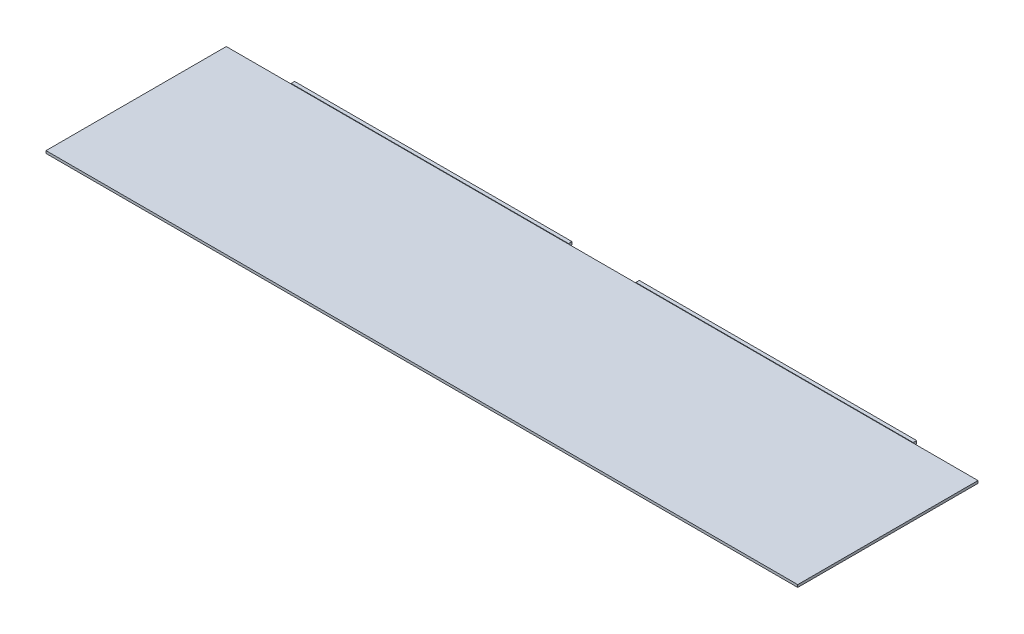
SolidWorks part; units mm, degrees
material "6061-T6 (SS)"
ref_plane "X-Y Datum" through (0, 0, 0) normal (0, 0, 1) x (1, 0, 0)
ref_plane "X-Z Datum" through (0, 0, 0) normal (0, 1, 0) x (1, 0, 0)
ref_plane "Y-Z Datum" through (0, 0, 0) normal (1, 0, 0) x (0, 0, -1)
sketch "Sketch1" plane through (0, 0, 0) normal (0, 1, 0) x (1, 0, 0)
  line L1 (-344.2208, 82.55) -> (344.2208, 82.55)
  line L2 (-344.2208, 82.55) -> (-344.2208, -82.55)
  line L3 (-344.2208, -82.55) -> (344.2208, -82.55)
  line L4 (344.2208, 82.55) -> (344.2208, -82.55)
  line L5 (-344.2208, 82.55) -> (344.2208, -82.55) construction
  line L6 (-344.2208, -82.55) -> (344.2208, 82.55) construction
  point P0 (0, 0)
  dimension "D1" = 688.4416
  dimension "D2" = 165.1
extrude "Boss-Extrude1" add sketch "Sketch1" along normal mid plane 2.286
sketch "Sketch2" plane through (0, 0, -82.55) normal (0, 0, -1) x (-1, 0, 0)
  line L20 (-344.2208, -1.143) -> (344.2208, -1.143) construction
  line L21 (-284.8229, -1.143) -> (-30.8229, -1.143)
  line L22 (30.8229, -1.143) -> (284.8229, -1.143)
  line L40 (30.8229, -1.143) -> (30.8229, 1.5875)
  line L41 (30.8229, 1.5875) -> (284.8229, 1.5875)
  line L42 (284.8229, 1.5875) -> (284.8229, -1.143)
  line L56 (-284.8229, -1.143) -> (-284.8229, 1.5875)
  line L57 (-284.8229, 1.5875) -> (-30.8229, 1.5875)
  line L58 (-30.8229, 1.5875) -> (-30.8229, -1.143)
extrude "Boss-Extrude2" add sketch "Sketch2" along normal blind 3.175
